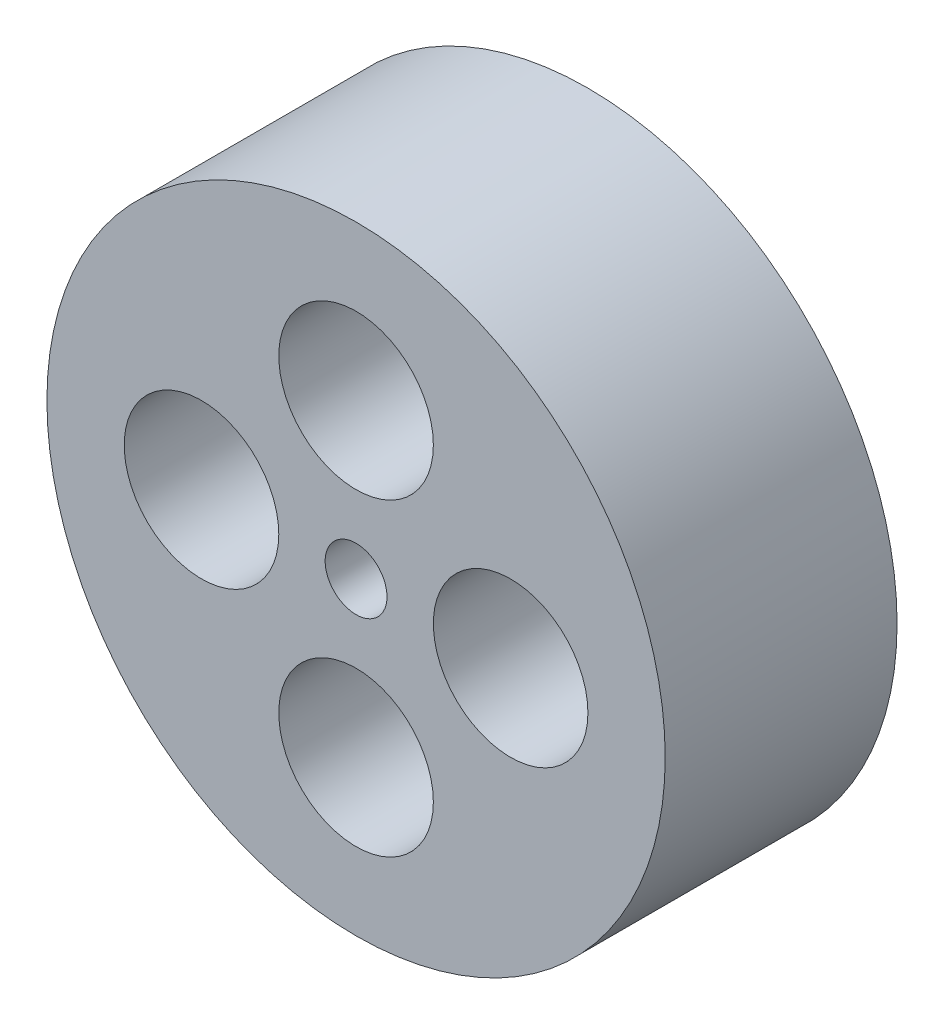
SolidWorks part; units mm, degrees
ref_plane "Front Plane" through (0, 0, 0) normal (0, 0, 1) x (1, 0, 0)
ref_plane "Top Plane" through (0, 0, 0) normal (0, 1, 0) x (1, 0, 0)
ref_plane "Right Plane" through (0, 0, 0) normal (1, 0, 0) x (0, 0, -1)
sketch "Sketch1" plane through (0, 0, 0) normal (0, 0, 1) x (1, 0, 0)
  line L0 (0, 0) -> (0, 40) construction
  circle A0 centre (0, 0) radius 40
  circle A1 centre (0, 0) radius 4
  circle A2 centre (0, 20) radius 10
  circle A3 centre (20, 0) radius 10
  circle A4 centre (0, -20) radius 10
  circle A5 centre (-20, 0) radius 10
  point P16 (0, 0)
  dimension "D1" = 80
  dimension "D2" = 8
  dimension "D3" = 20
  dimension "D4" = 4
extrude "Boss-Extrude1" add sketch "Sketch1" along normal blind 30
